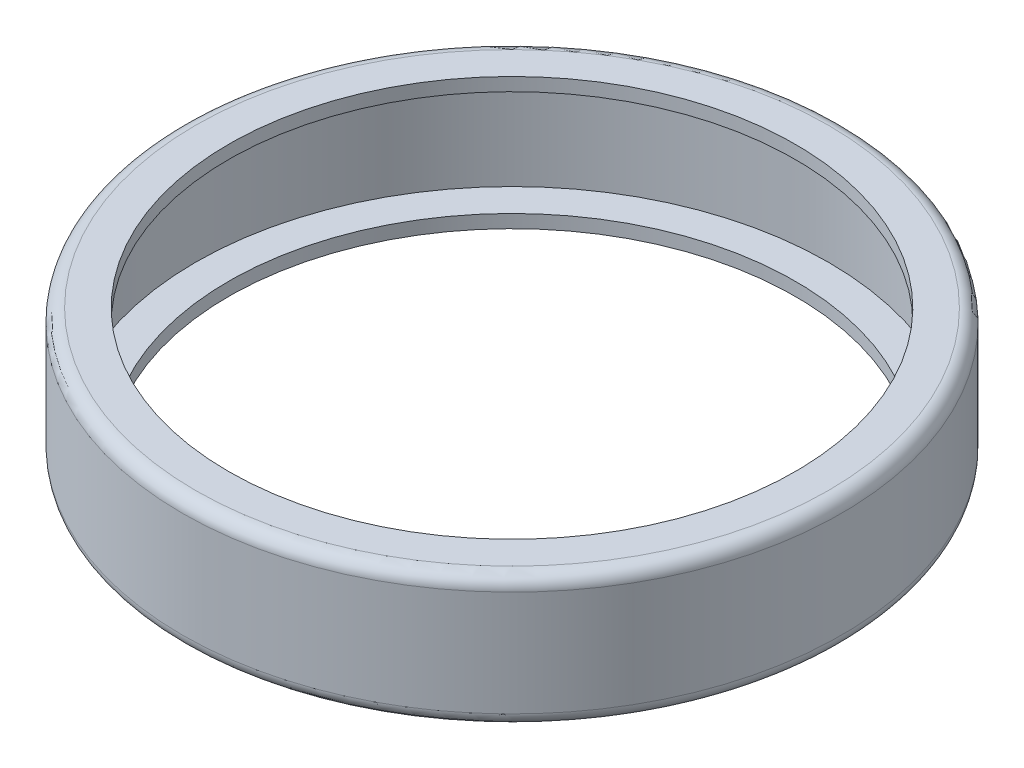
SolidWorks part; units mm, degrees
ref_plane "Front Plane" through (0, 0, 0) normal (0, 0, 1) x (1, 0, 0)
ref_plane "Top Plane" through (0, 0, 0) normal (0, 1, 0) x (1, 0, 0)
ref_plane "Right Plane" through (0, 0, 0) normal (1, 0, 0) x (0, 0, -1)
sketch "Sketch1" plane through (0, 0, 0) normal (0, 0, 1) x (1, 0, 0)
  line L0 (0, 17.7093) -> (0, -16.1534) construction
  line L1 (-63.5, 0) -> (0, 0) construction
  line L2 (-63.5, 0) -> (-54.61, 0)
  line L3 (-54.61, 0) -> (-54.61, 2.54)
  line L4 (-54.61, 2.54) -> (-60.96, 2.54)
  line L5 (-60.96, 2.54) -> (-60.96, 22.86)
  line L6 (-60.96, 22.86) -> (-54.61, 22.86)
  line L7 (-54.61, 22.86) -> (-54.61, 25.4)
  line L8 (-54.61, 25.4) -> (-63.5, 25.4)
  line L9 (-63.5, 25.4) -> (-63.5, 0)
  line L10 (-63.5, 0) -> (-63.8227, -0.3734)
  dimension "D1" = 25.4
  dimension "D2" = 8.89
  dimension "D3" = 2.54
  dimension "D4" = 2.54
  dimension "D5" = 63.5
revolve "Revolve1" add sketch "Sketch1" angle 360 about L0
fillet "Fillet1" radius 2.54 2 edges at (0, 0, 63.5) (0, 25.4, 63.5)
